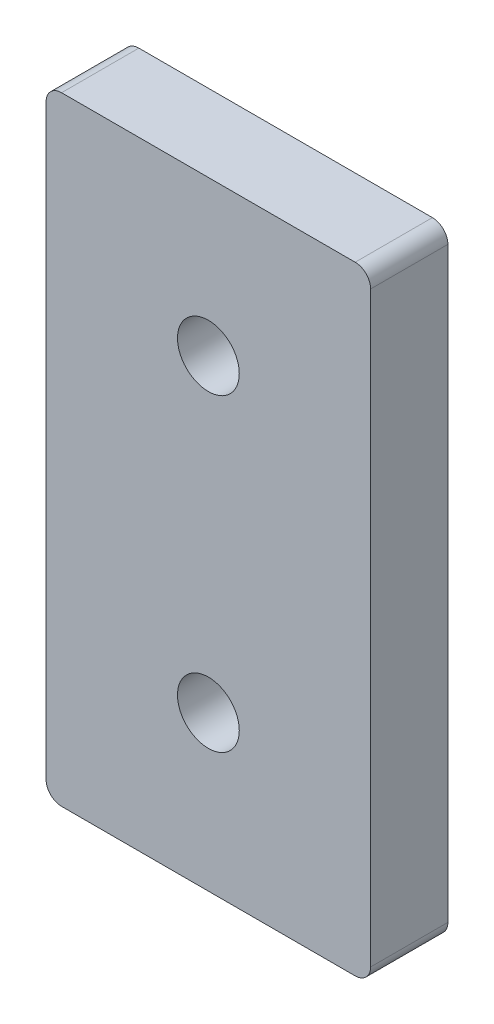
SolidWorks part; units mm, degrees
ref_plane "Front Plane" through (0, 0, 0) normal (0, 0, 1) x (1, 0, 0)
ref_plane "Top Plane" through (0, 0, 0) normal (0, 1, 0) x (1, 0, 0)
ref_plane "Right Plane" through (0, 0, 0) normal (1, 0, 0) x (0, 0, -1)
sketch "Sketch1" plane through (0, 0, 0) normal (0, 0, 1) x (1, 0, 0)
  line L0 (10.5, 40) -> (10.5, 0) construction
  line L1 (0, 0) -> (21, 0)
  line L2 (0, 0) -> (0, 40)
  line L3 (0, 40) -> (21, 40)
  line L4 (21, 0) -> (21, 40)
  circle A0 centre (10.5, 10) radius 2
  circle A1 centre (10.5, 30) radius 2
  dimension "D2" = 4
  dimension "D1" = 20
  dimension "D3" = 10
  dimension "D4" = 10
  dimension "D5" = 10.5
  dimension "D6" = 10.5
extrude "Boss-Extrude1" add sketch "Sketch1" along normal blind 5
fillet "Fillet1" radius 1 4 edges at (21, 0, 2.5) (0, 0, 2.5) (0, 40, 2.5) (21, 40, 2.5)
